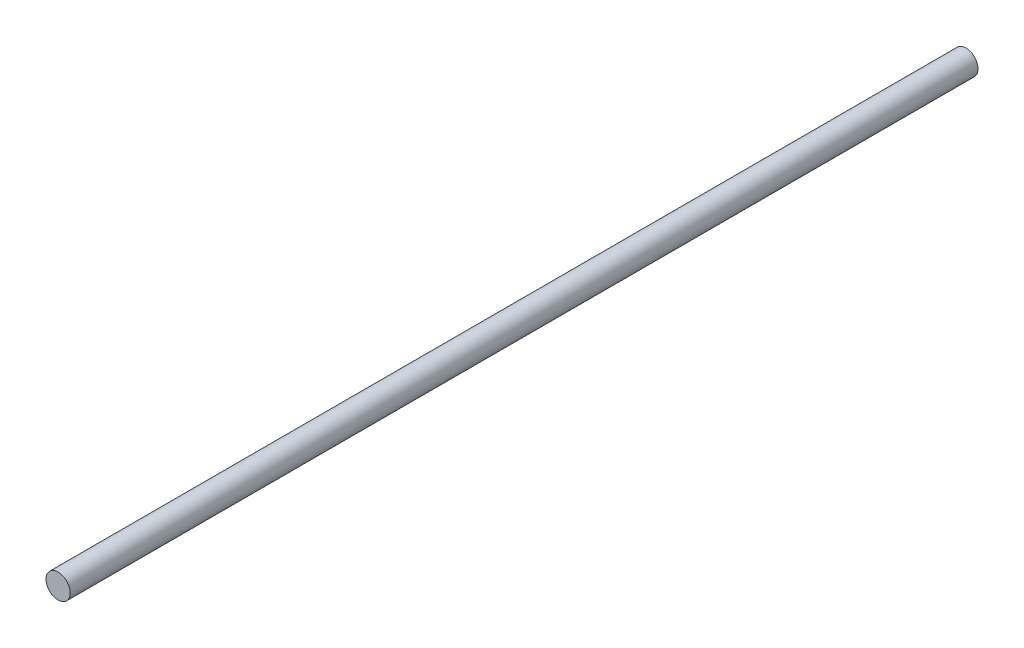
SolidWorks part; units mm, degrees
material "Hexcel AS4C (3000 Filaments)"
ref_plane "Front Plane" through (0, 0, 0) normal (0, 0, 1) x (1, 0, 0)
ref_plane "Top Plane" through (0, 0, 0) normal (0, 1, 0) x (1, 0, 0)
ref_plane "Right Plane" through (0, 0, 0) normal (1, 0, 0) x (0, 0, -1)
sketch "Sketch1" plane through (0, 0, 0) normal (0, 0, 1) x (1, 0, 0)
  circle A0 centre (0, 0) radius 1
  dimension "D1" = 2
extrude "Boss-Extrude1" add sketch "Sketch1" along normal blind 75
